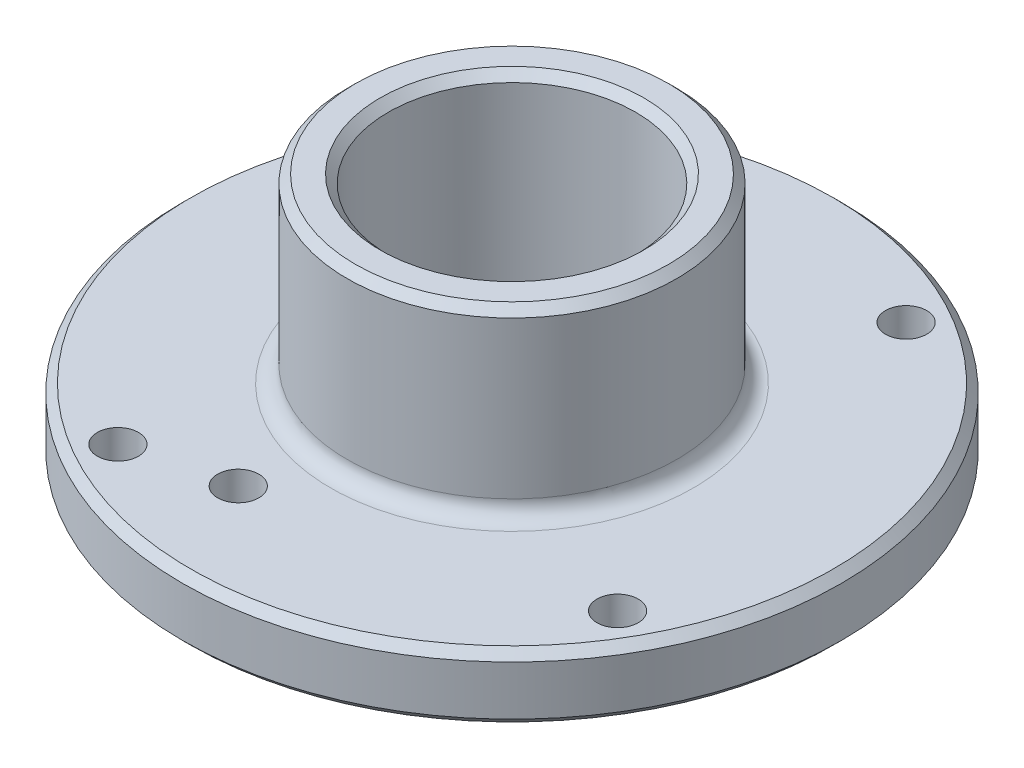
SolidWorks part; units mm, degrees
material "Cast Carbon Steel"
ref_plane "Front Plane" through (0, 0, 0) normal (0, 0, 1) x (1, 0, 0)
ref_plane "Top Plane" through (0, 0, 0) normal (0, 1, 0) x (1, 0, 0)
ref_plane "Right Plane" through (0, 0, 0) normal (1, 0, 0) x (0, 0, -1)
sketch "Sketch1" plane through (0, 0, 0) normal (0, 0, 1) x (1, 0, 0)
  line L0 (0, 0) -> (0, 33.2432) construction
  line L1 (-15, 0) -> (-15, 30)
  line L2 (-15, 30) -> (-20, 30)
  line L3 (-20, 30) -> (-20, 8)
  line L4 (-20, 8) -> (-40, 8)
  line L5 (-40, 8) -> (-40, 0)
  line L6 (-40, 0) -> (-15, 0)
  dimension "D1" = 30
  dimension "D2" = 40
  dimension "D3" = 5
  dimension "D4" = 15
  dimension "D5" = 8
revolve "Revolve1" add sketch "Sketch1" angle 360 about L0
fillet "Fillet1" radius 2 1 edges at (0, 8, -20)
chamfer "Chamfer1" distance 1 angle 45 4 edges at (0, 8, -40) (0, 0, -40) (0, 30, -15) (0, 30, -20)
chamfer "Chamfer2" distance 0.5 angle 45 1 edges at (0, 0, -15)
sketch "Sketch2" plane through (0, 0, 0) normal (0, -1, 0) x (1, 0, 0)
  line L0 (0, 0) -> (0, 38.3498) construction
  line L1 (0, 0) -> (-10.5226, 49.5047) construction
  circle A0 centre (-5.8215, 27.3881) radius 2.5
  dimension "D2" = 5
  dimension "D1" = 12
  dimension "D3" = 28
extrude "Cut-Extrude1" cut sketch "Sketch2" against normal through all both
sketch "Sketch5" plane through (0, 8, 0) normal (0, 1, 0) x (1, 0, 0)
  line L0 (0, 0) -> (-22.8065, -39.5019) construction
  line L1 (0, 0) -> (0, -11.5967) construction
  circle A0 centre (0, 0) radius 35 construction
  circle A1 centre (-17.5, -30.3109) radius 2.5
  circle A2 centre (-30.3109, 17.5) radius 2.5
  circle A3 centre (17.5, 30.3109) radius 2.5
  circle A4 centre (30.3109, -17.5) radius 2.5
  point P15 (0, 0)
  dimension "D1" = 5
  dimension "D2" = 70
  dimension "D4" = 30
  dimension "D3" = 4
extrude "Cut-Extrude3" cut sketch "Sketch5" against normal up to next
